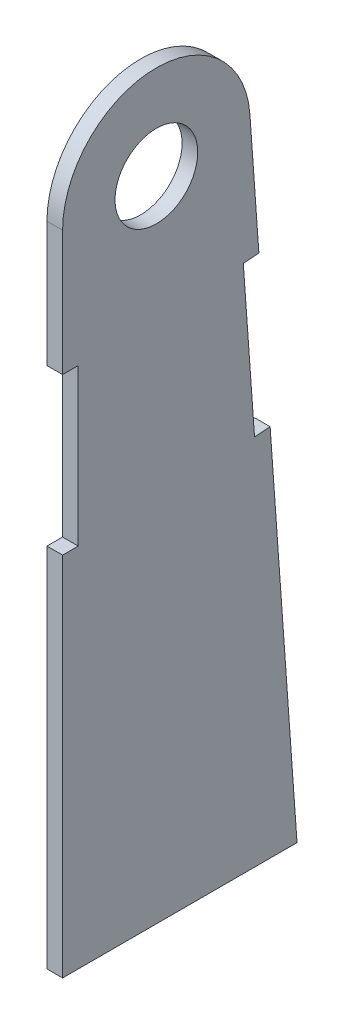
SolidWorks part; units mm, degrees
material "AISI 4130 Steel, annealed at 865C"
ref_plane "X-Y Datum" through (0, 0, 0) normal (0, 0, 1) x (1, 0, 0)
ref_plane "X-Z Datum" through (0, 0, 0) normal (0, 1, 0) x (1, 0, 0)
ref_plane "Y-Z Datum" through (0, 0, 0) normal (1, 0, 0) x (0, 0, -1)
sketch "Sketch1" plane through (0, 0, 0) normal (1, 0, 0) x (0, 0, -1)
  line L0 (0, -65.7746) -> (-9.525, -65.7746)
  line L1 (-9.525, -65.7746) -> (-9.525, 0)
  line L2 (0, -65.7746) -> (14.2875, -65.7746)
  line L3 (14.2875, -65.7746) -> (9.5004, 0.6843)
  line L4 (0, -65.7746) -> (0, 0) construction
  line L5 (-9.525, -28.575) -> (-7.9375, -28.575)
  line L10 (-9.525, -28.575) -> (-9.525, -12.7)
  line L11 (-7.9375, -28.575) -> (-7.9375, -12.7)
  line L12 (-9.525, -12.7) -> (-7.9375, -12.7)
  line L13 (11.5534, -27.8168) -> (10.4128, -11.9829)
  line L14 (11.5534, -27.8168) -> (9.97, -27.9309)
  line L15 (10.4128, -11.9829) -> (8.8294, -12.0969)
  line L16 (9.97, -27.9309) -> (8.8294, -12.0969)
  arc A0 (9.5004, 0.6843) -> (-9.525, 0) centre (0, 0) ccw
  dimension "D1" = 9.525
  dimension "D2" = 14.2875
  dimension "D3" = 9.525
  dimension "D4" = 65.7746
  dimension "D5" = 1.5875
  dimension "D6" = 15.875
  dimension "D7" = 12.7
  dimension "D8" = 12.7
extrude "Boss-Extrude1" add sketch "Sketch1" along normal blind 1.5875
hole_wizard "M8 Clearance Hole1" positions "Sketch2" profile "Sketch3" hole size "M8" standard "ANSI Metric" end condition through all
sketch "Sketch2" plane through (1.5875, 0, 0) normal (1, 0, 0) x (0, 0, -1)
  point P0 (0, 0)
sketch "Sketch3" plane through (1.5875, 0, 0) normal (0, 1, 0) x (0, 0, -1)
  line L0 (0, 0) -> (0, 1.5875)
  line L1 (0, 1.5875) -> (4.2, 1.5875)
  line L2 (4.2, 1.5875) -> (4.2, 0)
  line L5 (4.2, 0) -> (0, 0)
  line L11 (0, -6.35) -> (0, 107.95) construction
  dimension "Thru Hole Dia." = 8.4
  dimension "Thru Hole Depth" = 1.5875
sketch "Sketch4" plane through (1.5875, 0, 0) normal (1, 0, 0) x (0, 0, -1)
  line L2 (10.4128, -11.9829) -> (9.5004, 0.6843) construction
  line L3 (-9.525, -12.7) -> (-9.525, 0) construction
  line L5 (9.8132, -3.6584) -> (9.5004, 0.6843)
  line L6 (-9.525, -4.6718) -> (-9.525, 0)
  arc A3 (9.5004, 0.6843) -> (-9.525, 0) centre (0, 0) ccw construction
  arc A4 (9.5004, 0.6843) -> (-9.525, 0) centre (0, 0) ccw
  ellipse E0 centre (0.1656, -4.7625) end of major axis (0.3311, -17.4625) minor radius 9.69 (9.8132, -3.6584) -> (-9.525, -4.6718) ccw
  point P7 (0, 7.9375)
  dimension "D1" = 7.9375
  dimension "D2" = 4.7625
extrude "Cut-Extrude1" [suppressed] cut sketch "Sketch4" against normal through all
equation "\"D8@Sketch1\"=\"D7@Sketch1\""
